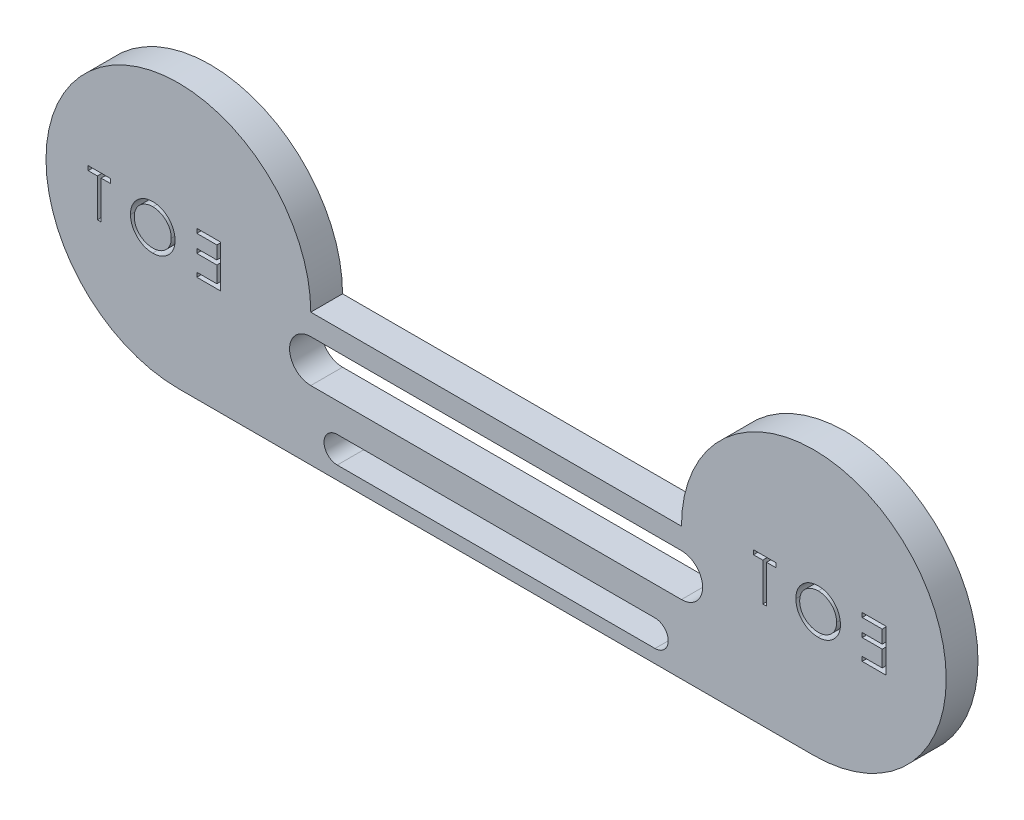
SolidWorks part; units mm, degrees
ref_plane "Front Plane" through (0, 0, 0) normal (0, 0, 1) x (1, 0, 0)
ref_plane "Top Plane" through (0, 0, 0) normal (0, 1, 0) x (1, 0, 0)
ref_plane "Right Plane" through (0, 0, 0) normal (1, 0, 0) x (0, 0, -1)
sketch "Sketch1" plane through (0, 0, 0) normal (0, 0, 1) x (1, 0, 0)
  line L0 (-63.0267, -23.9267) -> (6.9733, -23.9267)
  line L1 (-58.0267, -18.9267) -> (1.9733, -18.9267) construction
  line L2 (6.9733, 1.0733) -> (-63.0267, 1.0733)
  line L3 (-58.0267, -16.4267) -> (1.9733, -16.4267)
  line L4 (-58.0267, -21.4267) -> (1.9733, -21.4267)
  line L5 (-63.0267, -6.9267) -> (6.9733, -6.9267) construction
  line L6 (-63.0267, -2.9267) -> (6.9733, -2.9267)
  line L7 (-63.0267, -10.9267) -> (6.9733, -10.9267)
  line L8 (-63.0267, 45.604) -> (-63.0267, -52.202) construction
  line L9 (-63.0267, -23.9267) -> (-88.0267, -23.9267)
  line L10 (6.9733, 61.0924) -> (6.9733, -61.0934) construction
  line L11 (9.1197, -23.9267) -> (31.9733, -23.9267)
  line L12 (31.9733, -23.9267) -> (9.1197, -23.9267)
  line L13 (6.9733, -23.9267) -> (9.1197, -23.9267)
  arc A0 (-88.0267, -23.9267) -> (-63.0267, 1.0733) centre (-88.0267, 1.0733) cw
  arc A1 (31.9733, -23.9267) -> (6.9733, 1.0733) centre (31.9733, 1.0733) ccw
  arc A2 (-58.0267, -16.4267) -> (-58.0267, -21.4267) centre (-58.0267, -18.9267) ccw
  arc A3 (1.9733, -21.4267) -> (1.9733, -16.4267) centre (1.9733, -18.9267) ccw
  arc A4 (-63.0267, -10.9267) -> (-63.0267, -2.9267) centre (-63.0267, -6.9267) cw
  arc A5 (6.9733, -10.9267) -> (6.9733, -2.9267) centre (6.9733, -6.9267) ccw
  point P8 (-28.0267, -18.9267)
  point P15 (-28.0267, -6.9267)
  dimension "D3" = 5
  dimension "D6" = 17
extrude "Boss-Extrude2" add sketch "Sketch1" along normal blind 6
sketch "Sketch2" plane through (0, 0, 0) normal (0, 0, -1) x (-1, 0, 0)
  text T0 "  E O T" font "Century Gothic" height 8
  text T1 "E O T" font "Century Gothic" height 8
extrude "Cut-Extrude2" cut sketch "Sketch2" along direction (0, 0, 1) on the side against the normal blind 6
